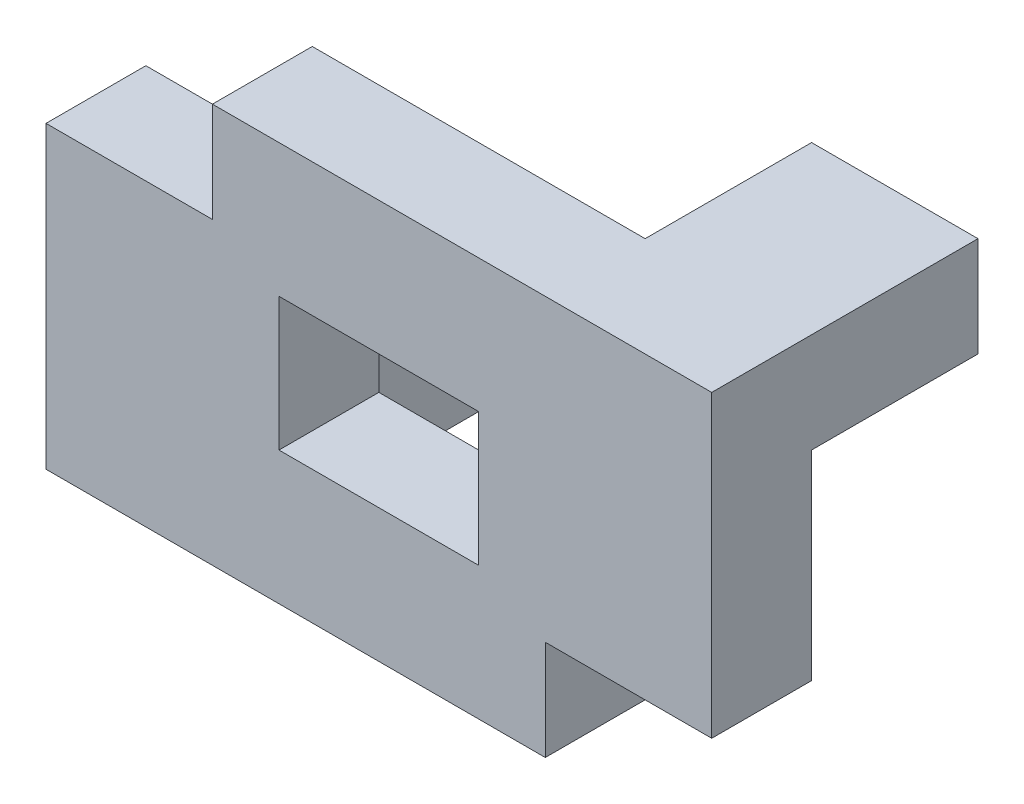
SolidWorks part; units mm, degrees
ref_plane "Front Plane" through (0, 0, 0) normal (0, 0, 1) x (1, 0, 0)
ref_plane "Top Plane" through (0, 0, 0) normal (0, 1, 0) x (1, 0, 0)
ref_plane "Right Plane" through (0, 0, 0) normal (1, 0, 0) x (0, 0, -1)
sketch "Sketch2" plane through (0, 0, 0) normal (0, 0, 1) x (1, 0, 0)
  line L1 (-50, 30) -> (50, 30)
  line L2 (-50, 30) -> (-50, -30)
  line L3 (-50, -30) -> (50, -30)
  line L4 (50, 30) -> (50, -30)
  dimension "D1" = 100
  dimension "D2" = 60
  dimension "D3" = 50
  dimension "D4" = 30
extrude "Boss-Extrude1" add sketch "Sketch2" along normal blind 15 contours L3 L4 L1 L2
sketch "Sketch3" plane through (0, 0, 0) normal (0, 0, -1) x (-1, 0, 0)
  line L1 (-50, 30) -> (-25, 30)
  line L2 (-50, 30) -> (-50, 15)
  line L3 (-50, 15) -> (-25, 15)
  line L4 (-25, 30) -> (-25, 15)
  line L5 (50, -30) -> (25, -30)
  line L6 (50, -30) -> (50, -15)
  line L7 (50, -15) -> (25, -15)
  line L8 (25, -30) -> (25, -15)
  dimension "D1" = 15
  dimension "D2" = 25
  dimension "D3" = 25
  dimension "D4" = 15
extrude "Boss-Extrude2" add sketch "Sketch3" along normal blind 25
sketch "Sketch4" plane through (0, 0, 0) normal (0, 0, -1) x (-1, 0, 0)
  line L1 (-50, -30) -> (-25, -30)
  line L2 (-50, -30) -> (-50, -15)
  line L3 (-50, -15) -> (-25, -15)
  line L4 (-25, -30) -> (-25, -15)
  line L5 (50, 30) -> (25, 30)
  line L6 (50, 30) -> (50, 15)
  line L7 (50, 15) -> (25, 15)
  line L8 (25, 30) -> (25, 15)
  dimension "D1" = 15
  dimension "D2" = 25
extrude "Cut-Extrude1" cut sketch "Sketch4" against normal blind 25
sketch "Sketch5" plane through (0, 0, 0) normal (0, 0, -1) x (-1, 0, 0)
  line L0 (-50, 15) -> (-50, -15) construction
  line L1 (-15, 10) -> (15, 10)
  line L2 (-15, 10) -> (-15, -10)
  line L3 (-15, -10) -> (15, -10)
  line L4 (15, 10) -> (15, -10)
  line L5 (25, -30) -> (-25, -30) construction
  dimension "D1" = 35
  dimension "D2" = 20
  dimension "D3" = 30
  dimension "D4" = 20
extrude "Cut-Extrude2" cut sketch "Sketch5" against normal blind 25
